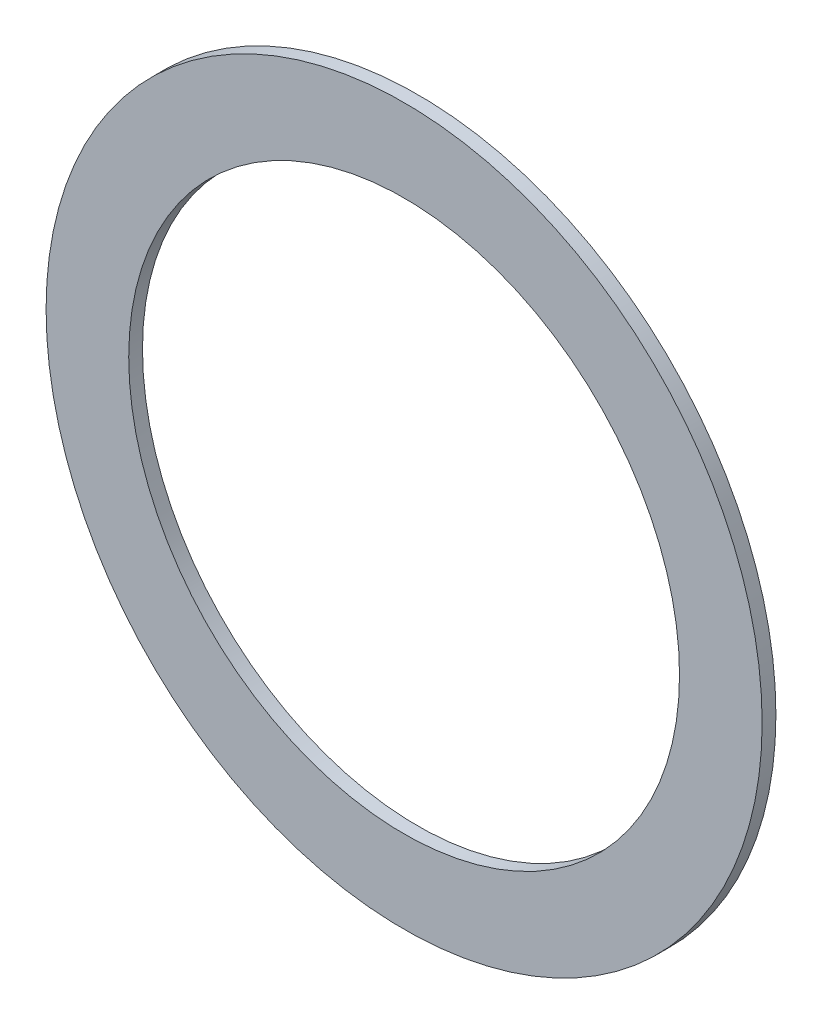
SolidWorks part; units mm, degrees
ref_plane "Plan1" through (0, 0, 0) normal (0, 0, 1) x (1, 0, 0)
ref_plane "Plan2" through (0, 0, 0) normal (0, 1, 0) x (1, 0, 0)
ref_plane "Plan3" through (0, 0, 0) normal (1, 0, 0) x (0, 0, -1)
sketch "Esquisse1" plane through (0, 0, 0) normal (0, 0, 1) x (1, 0, 0)
  circle A0 centre (0, 0) radius 20
  circle A1 centre (0, 0) radius 26
  dimension "D1" = 52
  dimension "D2" = 40
extrude "Base-Extrusion" add sketch "Esquisse1" along normal blind 1
